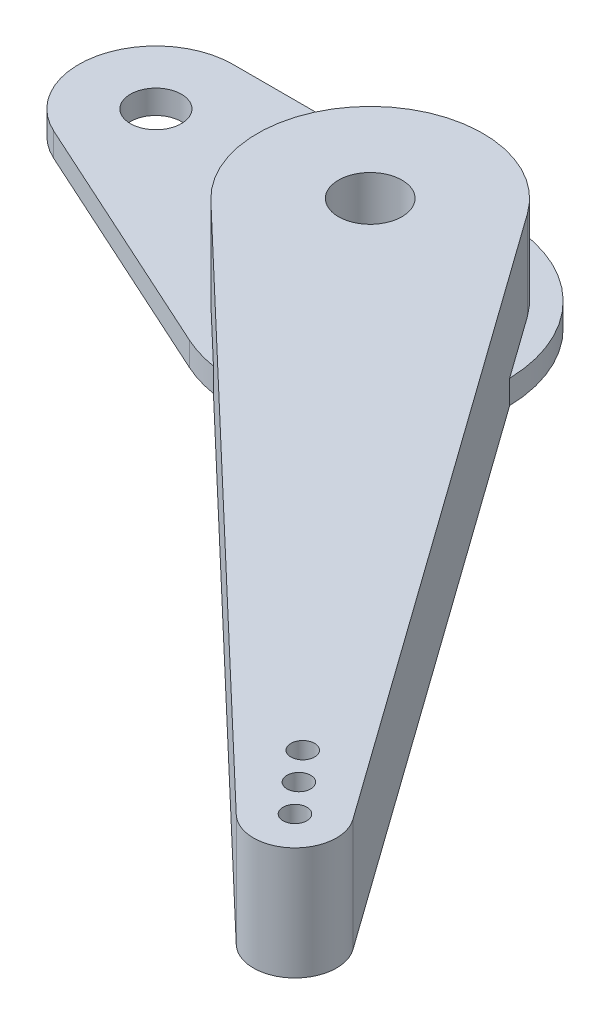
SolidWorks part; units mm, degrees
material "AISI 1020"
ref_plane "Plan de face" through (0, 0, 0) normal (0, 0, 1) x (1, 0, 0)
ref_plane "Plan de dessus" through (0, 0, 0) normal (0, 1, 0) x (1, 0, 0)
ref_plane "Plan de droite" through (0, 0, 0) normal (1, 0, 0) x (0, 0, -1)
sketch "Esquisse1" plane through (0, 0, 0) normal (0, 1, 0) x (1, 0, 0)
  line L0 (0, 11.5) -> (-23.0643, 11.5)
  line L1 (-25.756, -0.9165) -> (-4.7623, -10.4676)
  line L5 (-23.0643, 5) -> (0, 0) construction
  arc A0 (-4.7623, -10.4676) -> (0, 11.5) centre (0, 0) ccw
  arc A1 (-23.0643, 11.5) -> (-25.756, -0.9165) centre (-23.0643, 5) ccw
  circle A3 centre (0, 0) radius 2.675
  circle A4 centre (-23.0643, 5) radius 2.15
  point P10 (11.5, 0)
  point P11 (-29.4167, 6.3771)
  dimension "D1" = 23
  dimension "D2" = 6.5
  dimension "D8" = 5.35
  dimension "D9" = 4.3
  dimension "D3" = 23.6
extrude "Boss.-Extru.1" add sketch "Esquisse1" along normal blind 2
sketch "Esquisse2" plane through (0, 2, 0) normal (0, 1, 0) x (1, 0, 0)
  line L0 (0, 0) -> (-23.0643, 5) construction
  line L1 (0, 0) -> (49.8423, -10.8051) construction
  line L2 (49.8423, -10.8051) -> (41.7575, -48.0988) construction
  line L3 (7.7285, 5.5245) -> (44.6048, -46.0635)
  line L4 (-6.5552, -6.876) -> (39.3424, -50.6321)
  line L5 (0, 0) -> (41.7575, -48.0988) construction
  arc A0 (7.7285, 5.5245) -> (-6.5552, -6.876) centre (0, 0) ccw
  circle A1 centre (0, 0) radius 2.675
  arc A2 (39.3424, -50.6321) -> (44.6048, -46.0635) centre (41.7575, -48.0988) ccw
  circle A3 centre (41.7575, -48.0988) radius 1
  circle A4 centre (39.5941, -45.6069) radius 1
  circle A5 centre (37.4307, -43.115) radius 1
  dimension "D1" = 19
  dimension "D2" = 5.35
  dimension "D5" = 3.5
  dimension "D6" = 2
  dimension "D7" = 3.3
  dimension "D3" = 51
  dimension "D4" = 38.16
  dimension "D8" = 3.3
extrude "Boss.-Extru.2" add sketch "Esquisse2" along normal blind 7.5 and the other way blind 2
